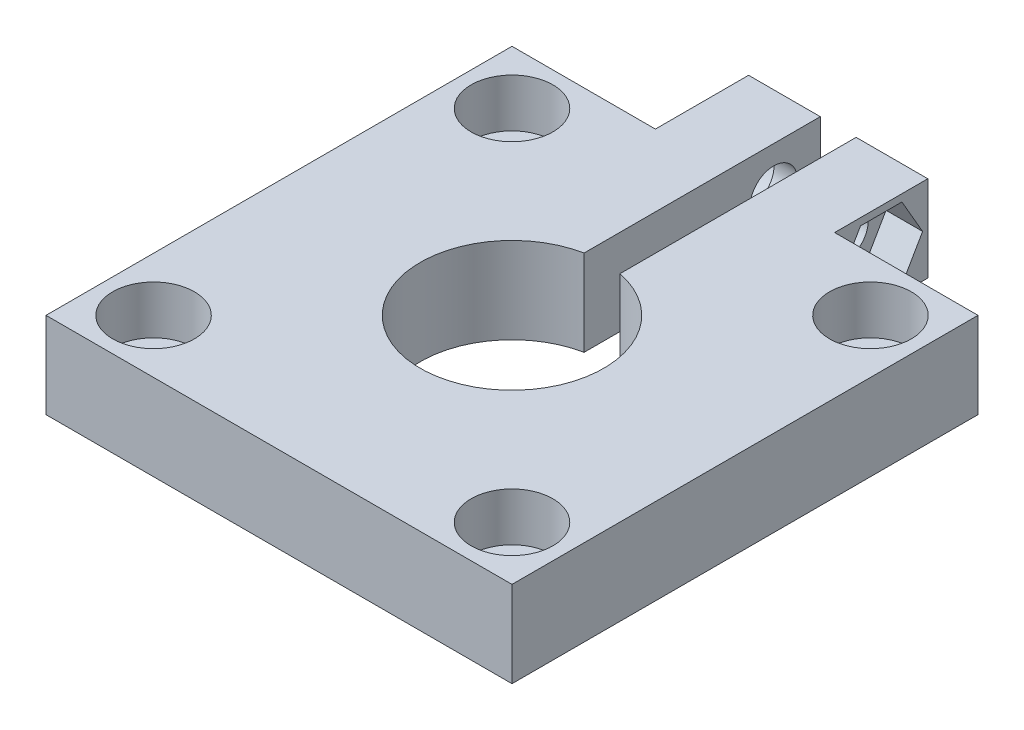
SolidWorks part; units mm, degrees
ref_plane "Front Plane" through (0, 0, 0) normal (0, 0, 1) x (1, 0, 0)
ref_plane "Top Plane" through (0, 0, 0) normal (0, 1, 0) x (1, 0, 0)
ref_plane "Right Plane" through (0, 0, 0) normal (1, 0, 0) x (0, 0, -1)
sketch "Sketch1" plane through (0, 0, 0) normal (0, 1, 0) x (1, 0, 0)
  line L1 (-32.5, 32.5) -> (32.5, 32.5)
  line L2 (-32.5, 32.5) -> (-32.5, -32.5)
  line L3 (-32.5, -32.5) -> (32.5, -32.5)
  line L4 (32.5, 32.5) -> (32.5, -32.5)
  line L5 (-32.5, 32.5) -> (32.5, -32.5) construction
  line L6 (-32.5, -32.5) -> (32.5, 32.5) construction
  point P0 (0, 0)
  dimension "D1" = 65
  dimension "D2" = 65
extrude "Boss-Extrude1" add sketch "Sketch1" along normal blind 12
sketch "Sketch3" plane through (0, 12, 0) normal (0, 1, 0) x (-1, 0, 0)
  circle A0 centre (0, 0) radius 12.8
  dimension "D1" = 25.6
extrude "Cut-Extrude1" cut sketch "Sketch3" against normal blind 12
sketch "Sketch4" plane through (0, 12, 0) normal (0, 1, 0) x (-1, 0, 0)
  line L0 (-32.5, -32.5) -> (32.5, -32.5) construction
  line L1 (2.5, -52.5) -> (-2.5, -52.5)
  line L2 (2.5, -52.5) -> (2.5, -12.5)
  line L3 (2.5, -12.5) -> (-2.5, -12.5)
  line L4 (-2.5, -52.5) -> (-2.5, -12.5)
  line L5 (2.5, -52.5) -> (-2.5, -12.5) construction
  line L6 (2.5, -12.5) -> (-2.5, -52.5) construction
  point P0 (0, -32.5)
  dimension "D1" = 40
extrude "Cut-Extrude2" cut sketch "Sketch4" against normal blind 12
sketch "Sketch5" plane through (0, 12, 0) normal (0, 1, 0) x (-1, 0, 0)
  line L1 (2.5, -32.5) -> (12.5, -32.5)
  line L2 (2.5, -32.5) -> (2.5, -45.5)
  line L3 (2.5, -45.5) -> (12.5, -45.5)
  line L4 (12.5, -32.5) -> (12.5, -45.5)
  dimension "D1" = 13
  dimension "D2" = 10
extrude "Boss-Extrude4" add sketch "Sketch5" against normal blind 12
pattern_linear "LPattern1" count 2 spacing 15 along (1, 0, 0) of "Boss-Extrude4"
hole_wizard "CBORE for M6 Hex Socket Head Cap Screw1" positions "Sketch7" profile "Sketch6" counterbore size "M6" standard "DIN" end condition through all
sketch "Sketch7" plane through (-12.5, 0, 0) normal (-1, 0, 0) x (0, 0, 1)
  line L0 (-45.5, 0) -> (-32.5, 0) construction
  line L1 (-45.5, 0) -> (-45.5, 12) construction
  point P0 (-39, 6)
  point P10 (-39, 0)
  point P11 (-45.5, 6)
  dimension "D1" = 0
  dimension "D2" = 0
sketch "Sketch6" plane through (-12.5, 6, -39) normal (0, 1, 0) x (0, 0, 1)
  line L0 (0, 0) -> (0, 45)
  line L1 (0, 45) -> (3.3, 45)
  line L3 (3.3, 45) -> (3.3, 6.75)
  line L4 (3.3, 6.75) -> (5.25, 6.75)
  line L5 (5.25, 6.75) -> (5.25, 0)
  line L7 (5.25, 0) -> (0, 0)
  line L11 (0, -6.35) -> (0, 107.95) construction
  dimension "Thru Hole Dia." = 6.6
  dimension "Thru Hole Depth" = 45
  dimension "C'Bore Dia." = 10.5
  dimension "C'Bore Depth" = 6.75
sketch "Sketch9" plane through (12.5, 0, 0) normal (1, 0, 0) x (0, 0, -1)
  line L0 (32.5, 0) -> (45.5, 0) construction
  line L1 (44.7735, 6) -> (41.8868, 11)
  line L2 (41.8868, 11) -> (36.1132, 11)
  line L3 (36.1132, 11) -> (33.2265, 6)
  line L4 (33.2265, 6) -> (36.1132, 1)
  line L5 (36.1132, 1) -> (41.8868, 1)
  line L6 (41.8868, 1) -> (44.7735, 6)
  line L8 (45.5, 0) -> (45.5, 12) construction
  circle A0 centre (39, 6) radius 5 construction
  point P1 (39, 0)
  point P11 (45.5, 6)
  dimension "D1" = 5
  dimension "D2" = 0
  dimension "D3" = 0
extrude "Cut-Extrude3" cut sketch "Sketch9" against normal blind 5.1
hole_wizard "CBORE for M6 Hex Socket Head Cap Screw2" positions "Sketch11" profile "Sketch10" counterbore size "M6" standard "DIN" end condition through all
sketch "Sketch11" plane through (0, 12, 0) normal (0, 1, 0) x (-1, 0, 0)
  point P0 (25, -25)
  dimension "D1" = 25
  dimension "D2" = 25
sketch "Sketch10" plane through (-25, 12, -25) normal (1, 0, 0) x (0, 0, 1)
  line L0 (0, 0) -> (0, 12)
  line L1 (0, 12) -> (3.75, 12)
  line L3 (3.75, 12) -> (3.75, 6.75)
  line L4 (3.75, 6.75) -> (5.7, 6.75)
  line L5 (5.7, 6.75) -> (5.7, 0)
  line L7 (5.7, 0) -> (0, 0)
  line L11 (0, -6.35) -> (0, 107.95) construction
  dimension "Thru Hole Dia." = 7.5
  dimension "Thru Hole Depth" = 12
  dimension "C'Bore Dia." = 11.4
  dimension "C'Bore Depth" = 6.75
hole_wizard "CBORE for M6 Hex Socket Head Cap Screw3" positions "Sketch13" profile "Sketch12" counterbore size "M6" standard "DIN" end condition through all
sketch "Sketch13" plane through (0, 12, 0) normal (0, 1, 0) x (-1, 0, 0)
  point P0 (-25, -25)
  dimension "D1" = 25
  dimension "D2" = 25
sketch "Sketch12" plane through (25, 12, -25) normal (1, 0, 0) x (0, 0, 1)
  line L0 (0, 0) -> (0, 12)
  line L1 (0, 12) -> (3.75, 12)
  line L3 (3.75, 12) -> (3.75, 6.75)
  line L4 (3.75, 6.75) -> (5.7, 6.75)
  line L5 (5.7, 6.75) -> (5.7, 0)
  line L7 (5.7, 0) -> (0, 0)
  line L11 (0, -6.35) -> (0, 107.95) construction
  dimension "Thru Hole Dia." = 7.5
  dimension "Thru Hole Depth" = 12
  dimension "C'Bore Dia." = 11.4
  dimension "C'Bore Depth" = 6.75
hole_wizard "CBORE for M6 Hex Socket Head Cap Screw4" positions "Sketch15" profile "Sketch14" counterbore size "M6" standard "DIN" end condition through all
sketch "Sketch15" plane through (0, 12, 0) normal (0, 1, 0) x (-1, 0, 0)
  point P0 (-25, 25)
  dimension "D1" = 25
  dimension "D2" = 25
sketch "Sketch14" plane through (25, 12, 25) normal (1, 0, 0) x (0, 0, 1)
  line L0 (0, 0) -> (0, 12)
  line L1 (0, 12) -> (3.75, 12)
  line L3 (3.75, 12) -> (3.75, 6.75)
  line L4 (3.75, 6.75) -> (5.7, 6.75)
  line L5 (5.7, 6.75) -> (5.7, 0)
  line L7 (5.7, 0) -> (0, 0)
  line L11 (0, -6.35) -> (0, 107.95) construction
  dimension "Thru Hole Dia." = 7.5
  dimension "Thru Hole Depth" = 12
  dimension "C'Bore Dia." = 11.4
  dimension "C'Bore Depth" = 6.75
hole_wizard "CBORE for M6 Hex Socket Head Cap Screw5" positions "Sketch17" profile "Sketch16" counterbore size "M6" standard "DIN" end condition through all
sketch "Sketch17" plane through (0, 12, 0) normal (0, 1, 0) x (-1, 0, 0)
  point P0 (25, 25)
  dimension "D1" = 25
  dimension "D2" = 25
sketch "Sketch16" plane through (-25, 12, 25) normal (1, 0, 0) x (0, 0, 1)
  line L0 (0, 0) -> (0, 12)
  line L1 (0, 12) -> (3.75, 12)
  line L3 (3.75, 12) -> (3.75, 6.75)
  line L4 (3.75, 6.75) -> (5.7, 6.75)
  line L5 (5.7, 6.75) -> (5.7, 0)
  line L7 (5.7, 0) -> (0, 0)
  line L11 (0, -6.35) -> (0, 107.95) construction
  dimension "Thru Hole Dia." = 7.5
  dimension "Thru Hole Depth" = 12
  dimension "C'Bore Dia." = 11.4
  dimension "C'Bore Depth" = 6.75
